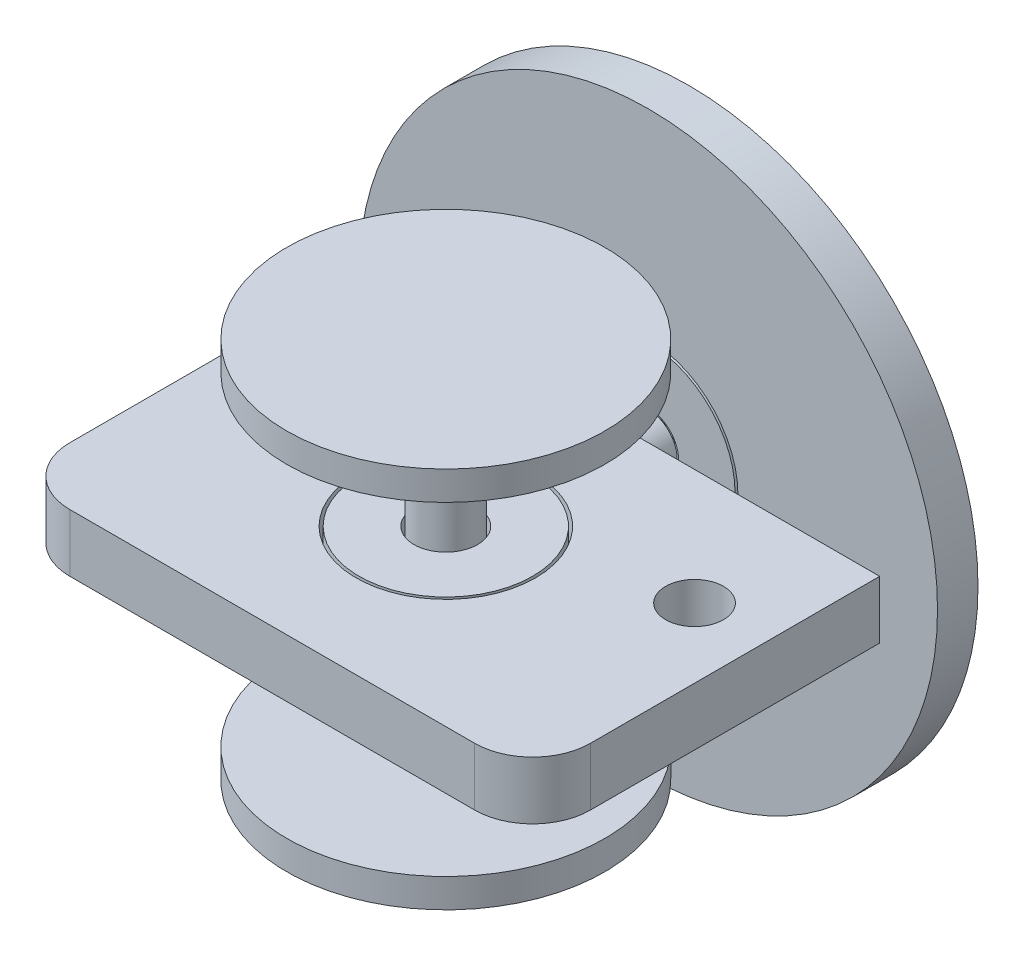
SolidWorks part; units mm, degrees
ref_plane "Front Plane" through (0, 0, 0) normal (0, 0, 1) x (1, 0, 0)
ref_plane "Top Plane" through (0, 0, 0) normal (0, 1, 0) x (1, 0, 0)
ref_plane "Right Plane" through (0, 0, 0) normal (1, 0, 0) x (0, 0, -1)
sketch "Sketch1" plane through (0, 0, 0) normal (0, 0, 1) x (1, 0, 0)
  circle A0 centre (0, 0) radius 20
  dimension "D1" = 40
extrude "Boss-Extrude1" add sketch "Sketch1" along normal blind 5
sketch "Sketch3" plane through (0, 0, 5) normal (0, 0, 1) x (1, 0, 0)
  circle A0 centre (0, 20) radius 1.5
  circle A1 centre (0, 0) radius 20 construction
  circle A2 centre (5.1764, 19.3185) radius 1.5
  circle A3 centre (10, 17.3205) radius 1.5
  circle A4 centre (14.1421, 14.1421) radius 1.5
  circle A5 centre (17.3205, 10) radius 1.5
  circle A6 centre (19.3185, 5.1764) radius 1.5
  circle A7 centre (20, 0) radius 1.5
  circle A8 centre (19.3185, -5.1764) radius 1.5
  circle A9 centre (17.3205, -10) radius 1.5
  circle A10 centre (14.1421, -14.1421) radius 1.5
  circle A11 centre (10, -17.3205) radius 1.5
  circle A12 centre (5.1764, -19.3185) radius 1.5
  circle A13 centre (0, -20) radius 1.5
  circle A14 centre (-5.1764, -19.3185) radius 1.5
  circle A15 centre (-10, -17.3205) radius 1.5
  circle A16 centre (-14.1421, -14.1421) radius 1.5
  circle A17 centre (-17.3205, -10) radius 1.5
  circle A18 centre (-19.3185, -5.1764) radius 1.5
  circle A19 centre (-20, 0) radius 1.5
  circle A20 centre (-19.3185, 5.1764) radius 1.5
  circle A21 centre (-17.3205, 10) radius 1.5
  circle A22 centre (-14.1421, 14.1421) radius 1.5
  circle A23 centre (-10, 17.3205) radius 1.5
  circle A24 centre (-5.1764, 19.3185) radius 1.5
  point P25 (0, 0)
  dimension "D1" = 3
  dimension "D2" = 24
extrude "Cut-Extrude1" cut sketch "Sketch3" along direction (0, 0, 1) on the side against the normal up to surface (5 mm away)
sketch "Sketch4" plane through (0, 0, 5) normal (0, 0, 1) x (1, 0, 0)
  circle A0 centre (0, 0) radius 5
  dimension "D1" = 10
extrude "Boss-Extrude2" add sketch "Sketch4" along normal blind 15
sketch "Sketch5" plane through (0, 0, 5) normal (0, 0, 1) x (1, 0, 0)
  circle A0 centre (0, 0) radius 15
  dimension "D1" = 30
extrude "Boss-Extrude3" add sketch "Sketch5" along direction (0, 0, 1) on the side of the normal blind 7 from offset 3
sketch "Sketch6" plane through (0, 0, 5) normal (0, 0, 1) x (1, 0, 0)
  circle A0 centre (0, 0) radius 5.25
  dimension "D1" = 10.5
extrude "Cut-Extrude4" cut sketch "Sketch6" along direction (0, 0, 1) on the side of the normal blind 7 from offset 3
sketch "Sketch7" plane through (0, 0, 15) normal (0, 0, 1) x (1, 0, 0)
  circle A0 centre (0, 0) radius 15.5
  circle A1 centre (0, 0) radius 50
  point P0 (0, 0)
  dimension "D3" = 31
  dimension "D1" = 100
extrude "Boss-Extrude4" add sketch "Sketch7" against normal blind 7
sketch "Sketch8" plane through (0, 0, 20) normal (0, 0, 1) x (1, 0, 0)
  line L1 (-45, 5) -> (45, 5)
  line L2 (-45, 5) -> (-45, -5)
  line L3 (-45, -5) -> (45, -5)
  line L4 (45, 5) -> (45, -5)
  line L5 (-45, 5) -> (45, -5) construction
  line L6 (-45, -5) -> (45, 5) construction
  point P0 (0, 0)
  dimension "D1" = 10
  dimension "D2" = 90
extrude "Boss-Extrude5" add sketch "Sketch8" along normal blind 60
sketch "Sketch9" plane through (0, -5, 0) normal (0, -1, 0) x (1, 0, 0)
  line L0 (0, 80) -> (0, 20) construction
  line L1 (-45, 80) -> (45, 80) construction
  line L2 (-45, 50.8934) -> (-45, 50) construction
  line L3 (-45, 80) -> (-45, 20) construction
  line L5 (-45, 50) -> (45, 50) construction
  line L6 (45, 80) -> (45, 20) construction
  circle A0 centre (0, 50) radius 15.5
  dimension "D1" = 31
extrude "Cut-Extrude5" cut sketch "Sketch9" against normal up to surface (10 mm away) up to face at (0, 5, 44)
sketch "Sketch10" plane through (0, -5, 0) normal (0, -1, 0) x (1, 0, 0)
  circle A0 centre (0, 50) radius 15
  circle A1 centre (0, 50) radius 5.5
  dimension "D1" = 30
  dimension "D2" = 11
extrude "Boss-Extrude6" add sketch "Sketch10" along direction (0, 1, 0) on the side against the normal up to surface (10 mm away) separate body
fillet "Fillet1" radius 10 2 edges at (-45, 0, 80) (45, 0, 80)
sketch "Sketch11" plane through (0, -5, 0) normal (0, -1, 0) x (-1, 0, 0)
  circle A0 centre (0, -50) radius 5
  dimension "D1" = 10
extrude "Boss-Extrude7" add sketch "Sketch11" along normal blind 3 and the other way blind 33
sketch "Sketch13" plane through (0, -8, 0) normal (0, -1, 0) x (1, 0, 0)
  circle A0 centre (0, 50) radius 20
  dimension "D1" = 40
extrude "Boss-Extrude8" add sketch "Sketch13" along normal blind 5 contours A0
sketch "Sketch14" plane through (0, -13, 0) normal (0, -1, 0) x (1, 0, 0)
  circle A0 centre (0, 70) radius 1.5
  circle A1 centre (0, 50) radius 20 construction
  dimension "D1" = 3
extrude "Cut-Extrude6" cut sketch "Sketch14" against normal blind 5 contours A0
pattern_circular "CirPattern2" count 24 over 360 about axis through (0, 0, 50) along (0, 1, 0) of "Cut-Extrude6"
sketch "Sketch16" plane through (0, -13, 0) normal (0, -1, 0) x (1, 0, 0)
  circle A0 centre (0, 50) radius 5
  dimension "D1" = 10
extrude "Boss-Extrude9" add sketch "Sketch16" along normal blind 15
sketch "Sketch18" plane through (0, -28, 0) normal (0, -1, 0) x (1, 0, 0)
  circle A0 centre (0, 50) radius 27.5
  dimension "D1" = 55
extrude "Boss-Extrude10" add sketch "Sketch18" along normal blind 5
sketch "Sketch19" plane through (0, 28, 0) normal (0, 1, 0) x (1, 0, 0)
  circle A0 centre (0, -50) radius 27.5
  dimension "D1" = 55
extrude "Boss-Extrude11" add sketch "Sketch19" along normal blind 5
sketch "Sketch20" plane through (0, 5, 0) normal (0, 1, 0) x (1, 0, 0)
  line L0 (45, -20) -> (0, -20) construction
  line L1 (45, -70) -> (45, -20) construction
  circle A0 centre (33, -40) radius 5
  dimension "D1" = 10
  dimension "D2" = 20
  dimension "D3" = 12
extrude "Cut-Extrude7" cut sketch "Sketch20" along direction (0, -1, 0) on the side against the normal up to surface (10 mm away)
